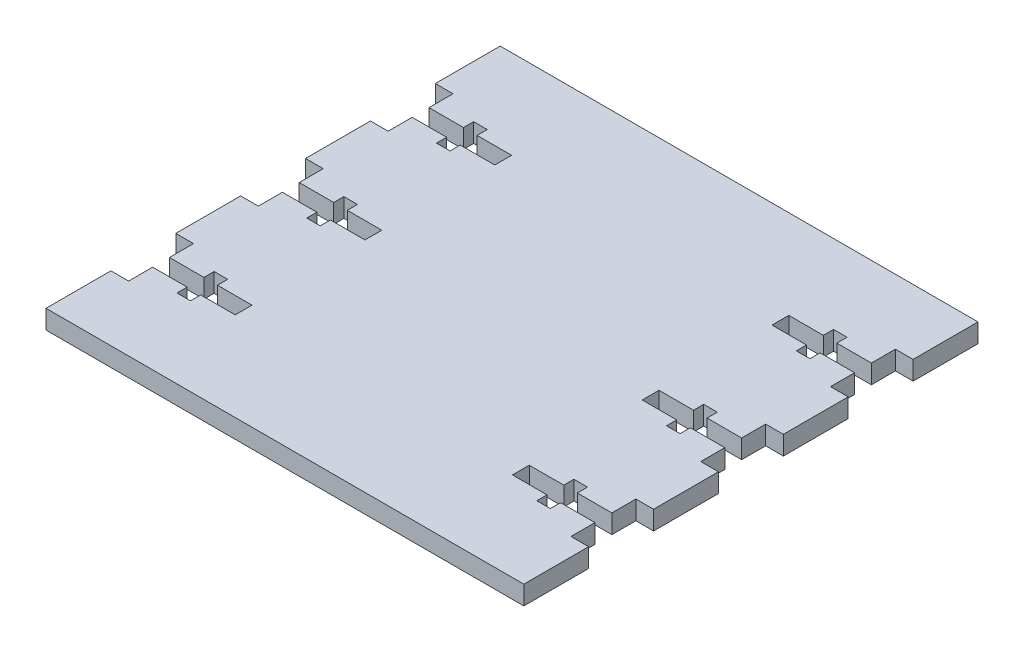
SolidWorks part; units mm, degrees
ref_plane "Front Plane" through (0, 0, 0) normal (0, 0, 1) x (1, 0, 0)
ref_plane "Top Plane" through (0, 0, 0) normal (0, 1, 0) x (1, 0, 0)
ref_plane "Right Plane" through (0, 0, 0) normal (1, 0, 0) x (0, 0, -1)
sketch "Sketch1" plane through (0, 0, 0) normal (0, 1, 0) x (1, 0, 0)
  line L0 (0, -38.5) -> (0, 38.5)
  line L1 (37.5, 0) -> (-37.5, 0)
  line L2 (-37.5, 38.5) -> (-37.5, -38.5)
  line L3 (-37.5, -38.5) -> (37.5, -38.5)
  line L4 (37.5, -38.5) -> (37.5, 38.5)
  line L5 (37.5, 38.5) -> (-37.5, 38.5)
  point P4 (0, 0)
  point P8 (0, 0)
extrude "Boss-Extrude1" add sketch "Sketch1" along normal blind 3.2 contours L2 L3 L4 L5
sketch "Sketch2" plane through (0, 3.2, 0) normal (0, 1, 0) x (1, 0, 0)
  line L0 (-37.5, 38.5) -> (-40.5, 38.5)
  line L1 (-40.5, 38.5) -> (-40.5, 27.5)
  line L2 (-40.5, 27.5) -> (-37.5, 27.5)
  line L3 (-37.5, 38.5) -> (-37.5, -38.5) construction
  line L4 (-37.5, 27.5) -> (-37.5, 38.5)
  line L5 (37.5, 38.5) -> (40.5, 38.5)
  line L6 (40.5, 38.5) -> (40.5, 27.5)
  line L7 (40.5, 27.5) -> (37.5, 27.5)
  line L8 (37.5, -38.5) -> (37.5, 38.5) construction
  line L9 (37.5, 27.5) -> (37.5, 38.5)
extrude "Boss-Extrude3" add sketch "Sketch2" against normal blind 3.2 contours L1 L2 L4 L0
pattern_linear "LPattern1" count 4 spacing 22 along (0, 0, 1) of "Boss-Extrude3"
sketch "Sketch4" plane through (0, 3.2, 0) normal (0, 1, 0) x (1, 0, 0)
  line L0 (37.5, 38.5) -> (40.5, 38.5)
  line L1 (40.5, 38.5) -> (40.5, 27.5)
  line L2 (40.5, 27.5) -> (37.5, 27.5)
  line L3 (37.5, -38.5) -> (37.5, 38.5) construction
  line L4 (37.5, 27.5) -> (37.5, 38.5)
extrude "Boss-Extrude5" add sketch "Sketch4" against normal blind 3.2 contours L1 L2 L4 L0
pattern_linear "LPattern2" count 4 spacing 22 along (0, 0, 1) of "Boss-Extrude5"
sketch "Sketch5" plane through (0, 3.2, 0) normal (0, 1, 0) x (1, 0, 0)
  line L0 (-37.5, 27.5) -> (-37.5, 22)
  line L2 (-37.5, 27.5) -> (-37.5, 16.5) construction
  line L3 (-37.5, 20.575) -> (-37.5, 23.425)
  line L4 (-37.5, 22) -> (-23.5, 22)
  line L5 (-23.5, 20.575) -> (-23.5, 23.425)
  line L6 (-23.5, 23.425) -> (-37.5, 23.425)
  line L7 (-37.5, 20.575) -> (-23.5, 20.575)
  line L8 (-30.5, 18.85) -> (-30.5, 25.15)
  line L9 (-29.35, 25.15) -> (-31.65, 25.15)
  line L10 (-29.35, 18.85) -> (-31.65, 18.85)
  line L11 (-31.65, 18.85) -> (-31.65, 25.15)
  line L12 (-29.35, 18.85) -> (-29.35, 25.15)
  point P9 (-37.5, 22)
  point P13 (-23.5, 22)
  point P16 (-30.5, 22)
  point P19 (-30.5, 25.15)
  point P22 (-30.5, 18.85)
extrude "Cut-Extrude1" cut sketch "Sketch5" against normal through all contours L7 L5 L6 L3 | L11 L9 L12 L10
pattern_linear "LPattern3" count 3 spacing 22 along (0, 0, 1) of "Cut-Extrude1"
sketch "Sketch6" plane through (0, 3.2, 0) normal (0, 1, 0) x (1, 0, 0)
  line L0 (0, 38.5) -> (0, -38.5)
  line L1 (-40.5, -38.5) -> (40.5, -38.5) construction
  point P6 (0, 0)
mirror "Mirror1" about plane through (0, 0, 0) normal (1, 0, 0) of "LPattern3", "Cut-Extrude1"
